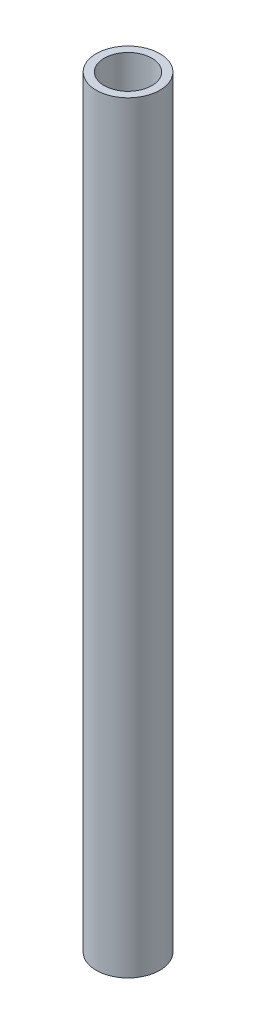
SolidWorks part; units mm, degrees
ref_plane "Front Plane" through (0, 0, 0) normal (0, 0, 1) x (1, 0, 0)
ref_plane "Top Plane" through (0, 0, 0) normal (0, 1, 0) x (1, 0, 0)
ref_plane "Right Plane" through (0, 0, 0) normal (1, 0, 0) x (0, 0, -1)
sketch "Sketch1" plane through (0, 0, 0) normal (0, 1, 0) x (1, 0, 0)
  circle A0 centre (0, 0) radius 19.05
  circle A1 centre (0, 0) radius 25.4
  dimension "D1" = 50.8
  dimension "D2" = 6.35
extrude "Boss-Extrude1" add sketch "Sketch1" along normal blind 609.6
equation "\"Pstrut_L\"= 24in'Primary Strut Length"
equation "\"Pstrut_T\"= 0.25in'Primary Strut Thickness"
equation "\"Pstrut_D\"= 2in'Primary Strut Diameter "
equation "\"Sstrut_T\" = 0.25in'Secondary Strut Thickness"
equation "\"Sstrut_L\"= 24in'Secondary Strut Length"
equation "\"Sstrut_D\"= 2in'Secondary Strut Diameter"
equation "\"LegStance\"= 7in"
equation "\"D1@Sketch1\"=\"Sstrut_D\""
equation "\"D2@Sketch1\"=\"Sstrut_T\""
equation "\"D1@Boss-Extrude1\"=\"Sstrut_L\""
